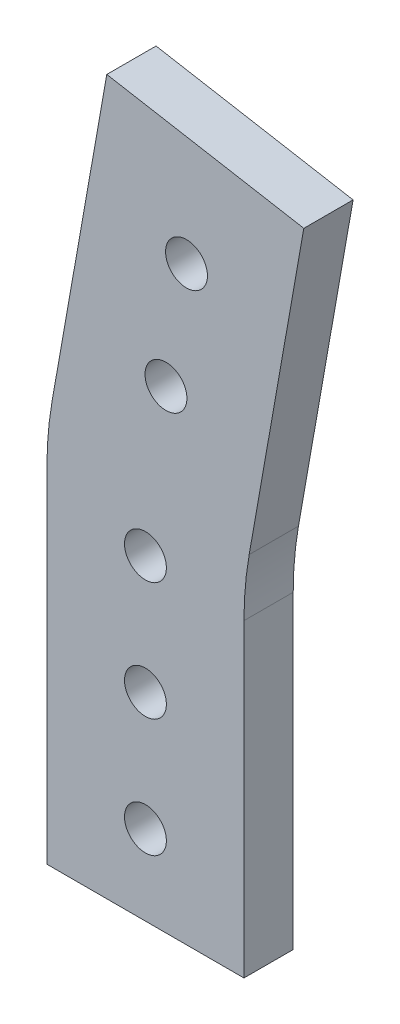
SolidWorks part; units mm, degrees
material "Thornel Mat VMA"
ref_plane "前视基准面" through (0, 0, 0) normal (0, 0, 1) x (1, 0, 0)
ref_plane "上视基准面" through (0, 0, 0) normal (0, 1, 0) x (1, 0, 0)
ref_plane "右视基准面" through (0, 0, 0) normal (1, 0, 0) x (0, 0, -1)
sketch "草图1" plane through (0, 0, 0) normal (0, 0, 1) x (1, 0, 0)
  line L0 (0, 0) -> (0, 38)
  line L4 (20, 34.4735) -> (20, 0)
  line L5 (20, 0) -> (0, 0)
  line L6 (0, 38) -> (6.0777, 72.4683)
  line L7 (10, 36.2367) -> (10, 0) construction
  line L8 (0, 38) -> (10, 36.2367) construction
  line L9 (10, 36.2367) -> (20, 34.4735) construction
  line L10 (0, 28) -> (20, 28) construction
  line L11 (10, 36.2367) -> (10, 28) construction
  line L12 (6.0777, 72.4683) -> (26.0777, 68.9417)
  line L13 (26.0777, 68.9417) -> (20, 34.4735)
  line L14 (20, 34.4735) -> (0, 34.4735) construction
  line L15 (10, 36.2367) -> (16.0777, 70.705) construction
  line L16 (12.0838, 48.0544) -> (22.0838, 46.2912) construction
  line L17 (14.1676, 59.8721) -> (24.1676, 58.1088) construction
  circle A0 centre (10, 32.1184) radius 2.125
  circle A1 centre (10, 20.1184) radius 2.125
  circle A2 centre (10, 8.1184) radius 2.125
  circle A5 centre (14.1676, 59.8721) radius 2.125
  circle A6 centre (12.0838, 48.0544) radius 2.125
  point P12 (10, 32.1184)
  dimension "D6" = 4.25
  dimension "D1" = 20
  dimension "D2" = 35
  dimension "D3" = 10
  dimension "D4" = 38
  dimension "D5" = 10
  dimension "D7" = 12
  dimension "D8" = 12
  dimension "D9" = 12
  dimension "D10" = 12
other "对齐组1"
extrude "凸台-拉伸1" add sketch "草图1" along normal blind 5
fillet "圆角1" radius 35 2 edges at (0, 38, 2.5) (20, 34.4735, 2.5)
